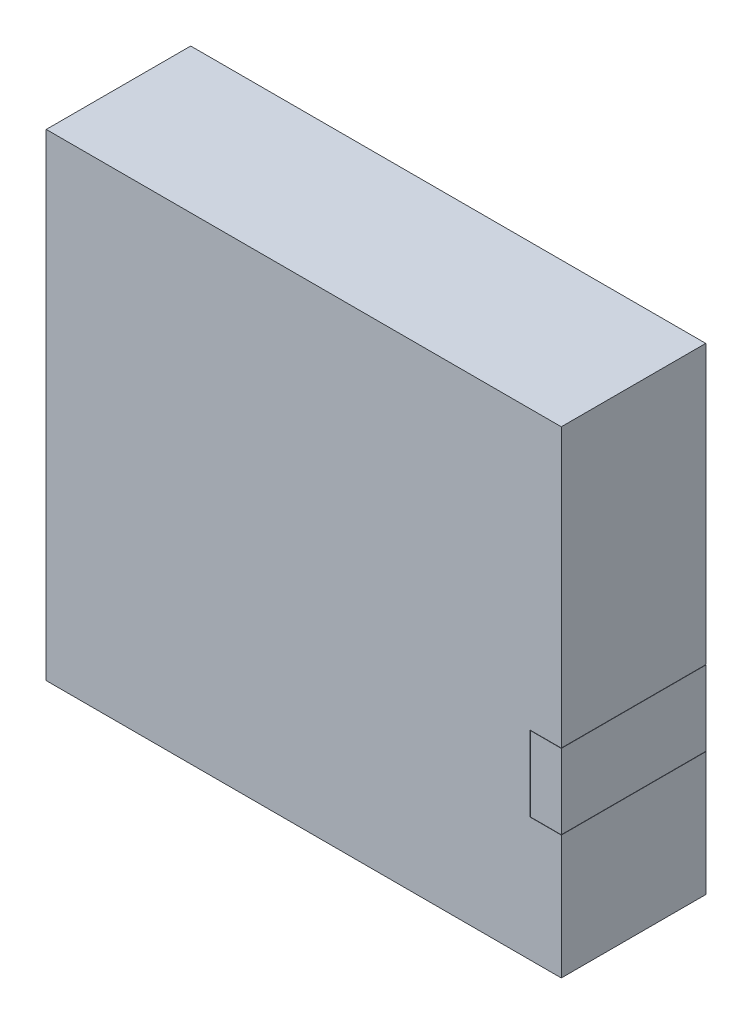
SolidWorks part; units mm, degrees
ref_plane "前视基准面" through (0, 0, 0) normal (0, 0, 1) x (1, 0, 0)
ref_plane "上视基准面" through (0, 0, 0) normal (0, 1, 0) x (1, 0, 0)
ref_plane "右视基准面" through (0, 0, 0) normal (1, 0, 0) x (0, 0, -1)
sketch "草图1" plane through (0, 0, 0) normal (0, 0, 1) x (1, 0, 0)
  line L1 (-41.5516, 22.2466) -> (40.4484, 22.2466)
  line L2 (-41.5516, 22.2466) -> (-41.5516, -53.7534)
  line L3 (-41.5516, -53.7534) -> (40.4484, -53.7534)
  line L4 (40.4484, 22.2466) -> (40.4484, -53.7534)
  dimension "D1" = 82
  dimension "D2" = 76
extrude "凸台-拉伸1" add sketch "草图1" along normal blind 23
sketch "草图2" plane through (0, 0, 23) normal (0, 0, 1) x (1, 0, 0)
  line L0 (40.4484, -53.7534) -> (40.4484, 22.2466) construction
  line L1 (40.4484, -34.0517) -> (35.4484, -34.0517)
  line L2 (40.4484, -34.0517) -> (40.4484, -22.0517)
  line L3 (40.4484, -22.0517) -> (35.4484, -22.0517)
  line L4 (35.4484, -34.0517) -> (35.4484, -22.0517)
  dimension "D1" = 12
  dimension "D2" = 5
extrude "切除-拉伸1" cut sketch "草图2" against normal blind 23
sketch "草图3" plane through (0, 0, 23) normal (0, 0, 1) x (1, 0, 0)
  line L1 (35.4484, -22.0517) -> (40.4484, -22.0517)
  line L2 (35.4484, -22.0517) -> (35.4484, -34.0517)
  line L3 (35.4484, -34.0517) -> (40.4484, -34.0517)
  line L4 (40.4484, -22.0517) -> (40.4484, -34.0517)
sketch "草图5" plane through (0, 0, 23) normal (0, 0, 1) x (1, 0, 0)
  line L0 (40.4484, -22.0517) -> (40.4484, -34.0517) construction
  line L1 (35.5484, -22.1017) -> (40.4484, -22.1017)
  line L2 (35.5484, -22.1017) -> (35.5484, -34.0017)
  line L3 (35.5484, -34.0017) -> (40.4484, -34.0017)
  line L4 (40.4484, -22.1017) -> (40.4484, -34.0017)
  line L5 (35.4484, -34.0517) -> (40.4484, -34.0517) construction
  dimension "D1" = 11.9
  dimension "D2" = 4.9
  dimension "D3" = 0
  dimension "D4" = 0.05
extrude "凸台-拉伸3" add sketch "草图5" against normal blind 23 separate body
